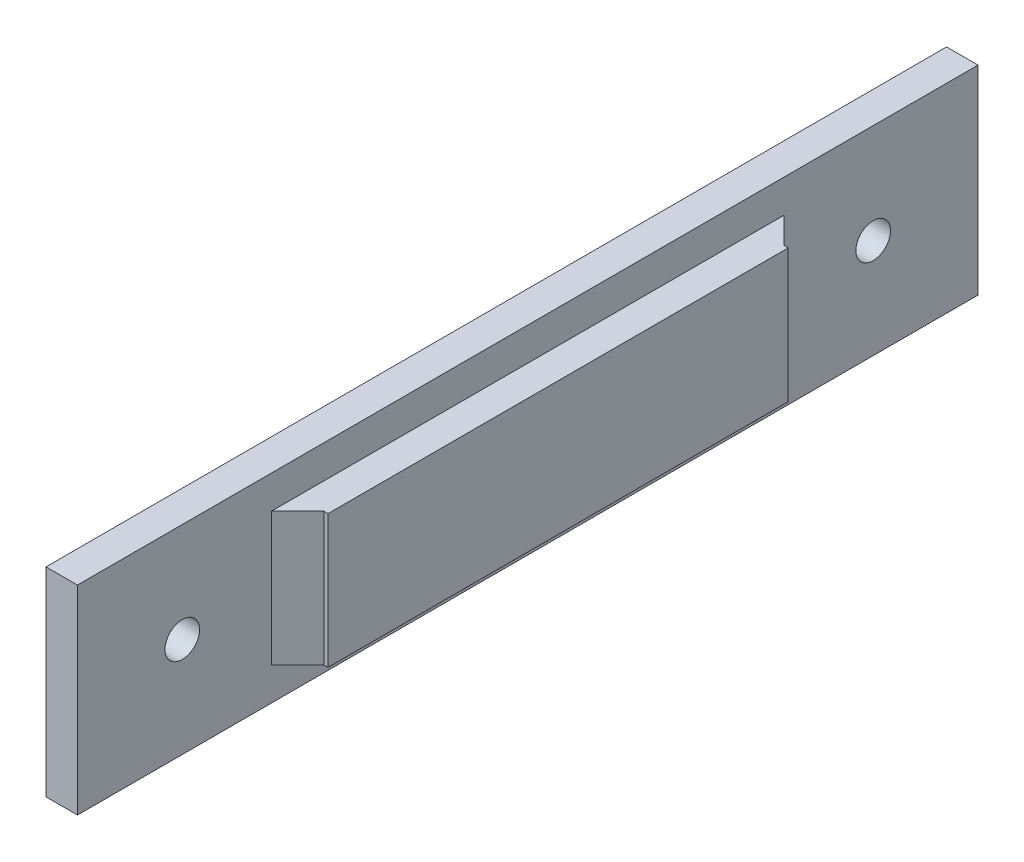
SolidWorks part; units mm, degrees
ref_plane "前视基准面" through (0, 0, 0) normal (0, 0, 1) x (1, 0, 0)
ref_plane "上视基准面" through (0, 0, 0) normal (0, 1, 0) x (1, 0, 0)
ref_plane "右视基准面" through (0, 0, 0) normal (1, 0, 0) x (0, 0, -1)
sketch "草图1" plane through (0, 0, 0) normal (0, 0, 1) x (1, 0, 0)
  line L1 (0, 0) -> (13, 0)
  line L2 (0, 0) -> (0, 13)
  line L3 (0, 13) -> (13, 13)
  line L4 (13, 0) -> (13, 13)
  dimension "D1" = 13
  dimension "D2" = 13
extrude "拉伸-薄壁1" add sketch "草图1" along normal blind 85.9 thin
sketch "草图2" plane through (-3, 0, 0) normal (-1, 0, 0) x (0, 0, 1)
  line L0 (0, 16) -> (0, -3) construction
  line L1 (85.9, 16) -> (85.9, -3) construction
  circle A0 centre (10, 6.5) radius 1.65
  circle A1 centre (75.9, 6.5) radius 1.65
  dimension "D1" = 3.3
  dimension "D2" = 3.3
  dimension "D3" = 10
  dimension "D4" = 10
extrude "切除-拉伸1" cut sketch "草图2" against normal blind 30
sketch "草图3" plane through (16, 0, 0) normal (1, 0, 0) x (0, 0, -1)
  line L1 (-85.9, 16) -> (0, 16)
  line L2 (-85.9, 16) -> (-85.9, -3)
  line L3 (-85.9, -3) -> (0, -3)
  line L4 (0, 16) -> (0, -3)
extrude "切除-拉伸2" cut sketch "草图3" against normal blind 16
sketch "草图4" plane through (0, 0, 0) normal (1, 0, 0) x (0, 0, -1)
  line L0 (0, 16) -> (0, -3) construction
  line L1 (-64.9, 12.85) -> (-21, 12.85)
  line L2 (-64.9, 12.85) -> (-64.9, 0.15)
  line L3 (-64.9, 0.15) -> (-21, 0.15)
  line L4 (-21, 12.85) -> (-21, 0.15)
  line L5 (-85.9, 16) -> (-85.9, -3) construction
  line L6 (-85.9, -3) -> (0, -3) construction
  line L7 (0, 16) -> (-85.9, 16) construction
  point P8 (-21, 6.5)
  dimension "D1" = 21
  dimension "D2" = 21
  dimension "D3" = 12.7
  dimension "D4" = 9.5
  dimension "D5" = 3.15
  dimension "D6" = 3.15
extrude "凸台-拉伸1" add sketch "草图4" along normal blind 2.9
chamfer "倒角1" distance 2.5 angle 45 2 edges at (0, 6.5, 21) (0, 6.5, 64.9)
